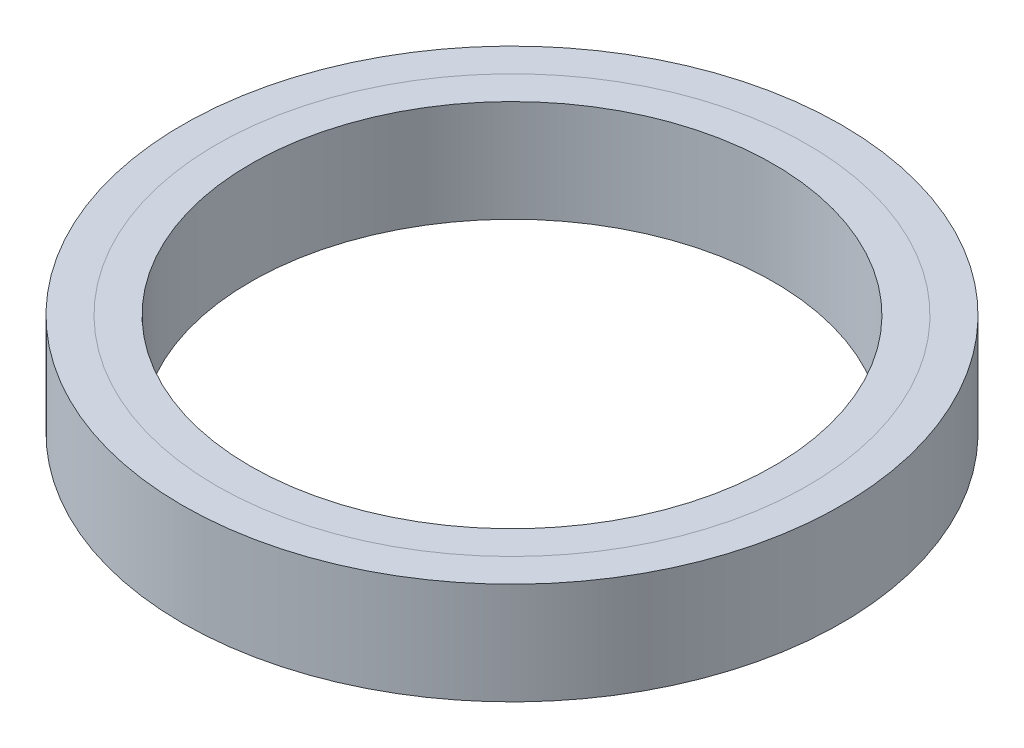
SolidWorks part; units mm, degrees
ref_plane "前视基准面" through (0, 0, 0) normal (0, 0, 1) x (1, 0, 0)
ref_plane "上视基准面" through (0, 0, 0) normal (0, 1, 0) x (1, 0, 0)
ref_plane "右视基准面" through (0, 0, 0) normal (1, 0, 0) x (0, 0, -1)
sketch "草图2" plane through (0, 0, 0) normal (0, 1, 0) x (1, 0, 0)
  circle A0 centre (0, 0) radius 38.5
  circle A1 centre (0, 0) radius 43.5
  dimension "D1" = 77
  dimension "D2" = 5
extrude "凸台-拉伸1" add sketch "草图2" along normal mid plane 15
sketch "草图3" plane through (0, 0, 0) normal (0, 1, 0) x (1, 0, 0)
  circle A0 centre (0, 0) radius 43.5
  circle A1 centre (0, 0) radius 48.5
  circle A2 centre (0, 0) radius 43.5 construction
  dimension "D1" = 5
extrude "凸台-拉伸2" add sketch "草图3" along normal mid plane 15 separate body
